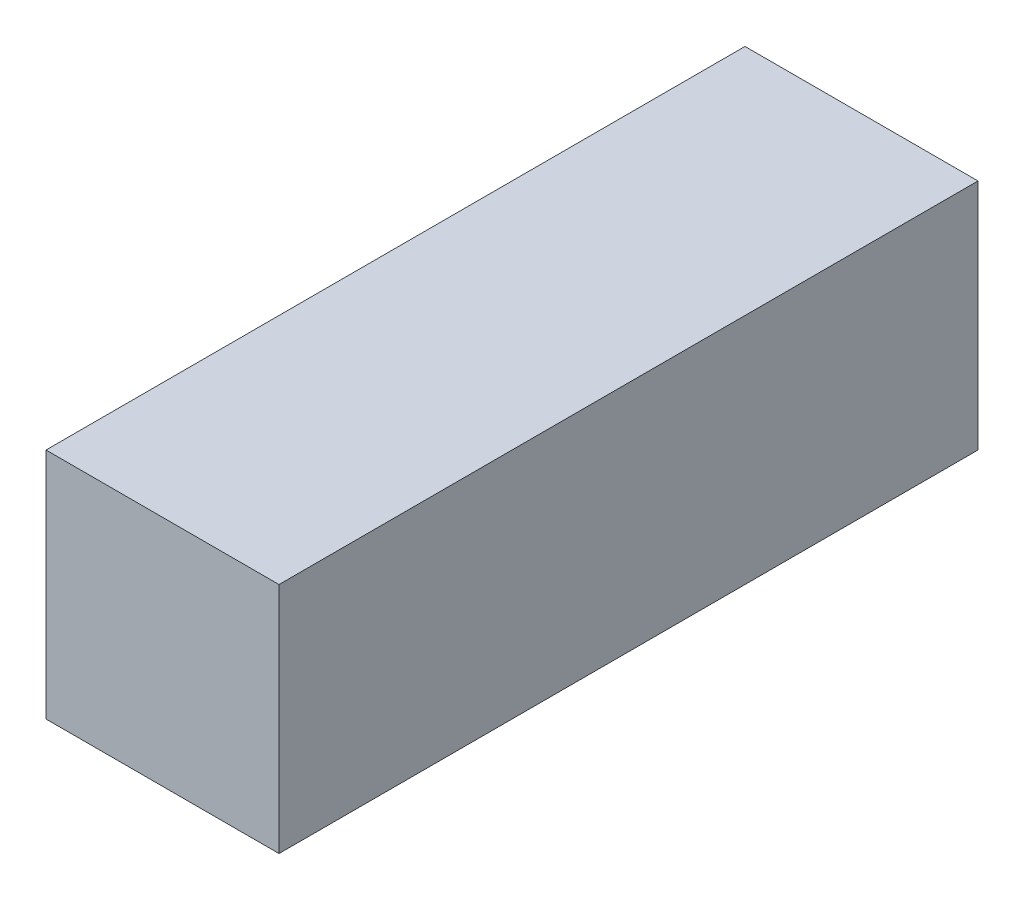
SolidWorks part; units mm, degrees
ref_plane "Front Plane" through (0, 0, 0) normal (0, 0, 1) x (1, 0, 0)
ref_plane "Top Plane" through (0, 0, 0) normal (0, 1, 0) x (1, 0, 0)
ref_plane "Right Plane" through (0, 0, 0) normal (1, 0, 0) x (0, 0, -1)
sketch "Sketch2" plane through (0, 0, 0) normal (0, 0, 1) x (1, 0, 0)
  line L1 (-41.7219, 26.4901) -> (58.2781, 26.4901)
  line L2 (-41.7219, 26.4901) -> (-41.7219, -73.5099)
  line L3 (-41.7219, -73.5099) -> (58.2781, -73.5099)
  line L4 (58.2781, 26.4901) -> (58.2781, -73.5099)
  dimension "D1" = 100
  dimension "D2" = 100
extrude "Boss-Extrude1" add sketch "Sketch2" along normal blind 300
